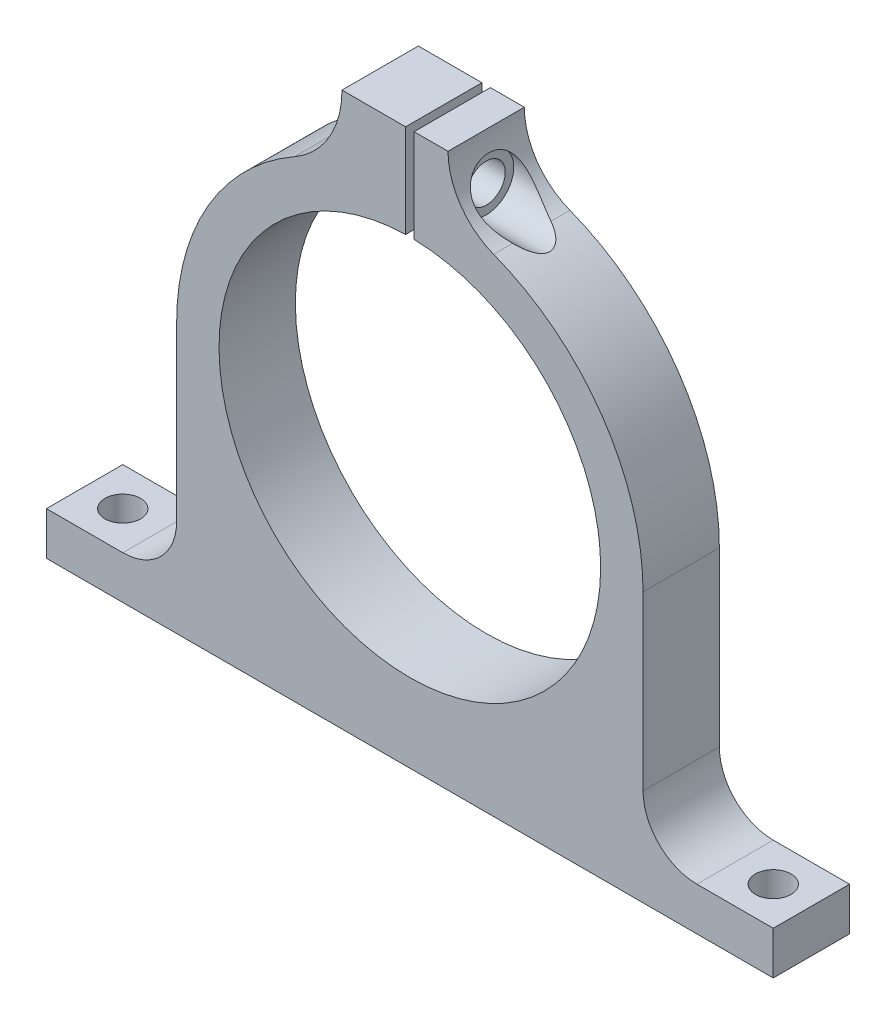
SolidWorks part; units mm, degrees
material "6061-T6 (SS)"
ref_plane "Front Plane" through (0, 0, 0) normal (0, 0, 1) x (1, 0, 0)
ref_plane "Top Plane" through (0, 0, 0) normal (0, 1, 0) x (1, 0, 0)
ref_plane "Right Plane" through (0, 0, 0) normal (1, 0, 0) x (0, 0, -1)
sketch "Sketch1" plane through (0, 0, 0) normal (0, 0, 1) x (1, 0, 0)
  line L0 (0, 0) -> (0, 55) construction
  line L1 (0, 0) -> (85.7, 0) construction
  line L2 (0, 0) -> (-85.7, 0) construction
  line L3 (85.7, -53.34) -> (85.7, -63.5)
  line L4 (85.7, -63.5) -> (-85.7, -63.5)
  line L5 (-85.7, -63.5) -> (-85.7, -53.34)
  line L6 (0, 55) -> (0, 67) construction
  line L7 (0, 67) -> (1, 67) construction
  line L8 (1, 67) -> (1, 44.9889)
  line L9 (1, 67) -> (9, 67)
  line L10 (-45, 0) -> (-55, 0) construction
  line L11 (0, 67) -> (-1, 67) construction
  line L12 (-1, 67) -> (-1, 44.9889)
  line L13 (-1, 67) -> (-16, 67)
  line L14 (-55, 0) -> (-55, -40.64)
  line L15 (-67.7, -53.34) -> (-85.7, -53.34)
  line L16 (55, 0) -> (55, -40.64)
  line L17 (67.7, -53.34) -> (85.7, -53.34)
  arc A0 (-1, 44.9889) -> (1, 44.9889) centre (0, 0) ccw
  arc A1 (55, 0) -> (19.76, 51.3278) centre (0, 0) ccw
  arc A2 (-27.1614, 47.8253) -> (-55, 0) centre (0, 0) ccw
  arc A3 (9, 67) -> (19.76, 51.3278) centre (25.7935, 67) ccw
  arc A4 (55, -40.64) -> (67.7, -53.34) centre (67.7, -40.64) ccw
  arc A5 (-55, -40.64) -> (-67.7, -53.34) centre (-67.7, -40.64) cw
  arc A6 (-27.1614, 47.8253) -> (-16, 67) centre (-38.0513, 67) ccw
  dimension "D1" = 90
  dimension "D3" = 12.7
  dimension "D4" = 18
  dimension "D2" = 10
  dimension "D5" = 10.16
  dimension "D6" = 12
  dimension "D7" = 1
  dimension "D8" = 8
  dimension "D9" = 1
  dimension "D10" = 15
  dimension "D11" = 63.5
extrude "main body" add sketch "Sketch1" along normal blind 18
sketch "Sketch7" plane through (1, 0, 0) normal (-1, 0, 0) x (0, 0, 1)
  line L0 (9, 44.9889) -> (9, 67) construction
  line L1 (18, 44.9889) -> (0, 44.9889) construction
  line L2 (18, 67) -> (0, 67) construction
  circle A0 centre (9, 55.9944) radius 3.5
  dimension "D1" = 7
ref_plane "Plane3" through (9, 0, 0) normal (-1, 0, 0) x (0, 0, 1)
sketch "Sketch10" plane through (9, 0, 0) normal (-1, 0, 0) x (0, 0, 1)
  circle A0 centre (9, 55.9944) radius 6.5
  dimension "D1" = 13
extrude "head counterbore" cut sketch "Sketch10" against normal blind 18
sketch "to table bolt locations" plane through (0, -53.34, 0) normal (0, 1, 0) x (1, 0, 0)
  line L0 (-76.7, 0) -> (-76.7, -18) construction
  line L1 (-67.7, 0) -> (-85.7, 0) construction
  line L2 (-67.7, -18) -> (-85.7, -18) construction
  line L3 (76.7, 0) -> (76.7, -18) construction
  line L4 (85.7, 0) -> (67.7, 0) construction
  line L5 (85.7, -18) -> (67.7, -18) construction
  circle A0 centre (-76.7, -9) radius 4.25
  circle A1 centre (76.7, -9) radius 4.25
  dimension "D1" = 8.5
sketch "Sketch12" plane through (9, 0, 0) normal (-1, 0, 0) x (0, 0, 1)
  line L0 (9, 44.9889) -> (9, 67) construction
  line L1 (18, 44.9889) -> (0, 44.9889) construction
  line L2 (18, 67) -> (0, 67) construction
  circle A0 centre (9, 55.9944) radius 4.25
  dimension "D1" = 8.5
hole_wizard "to table M8 Clearance Hole1" positions "Sketch13" profile "Sketch14" hole size "M8" standard "ANSI Metric" end condition through all
sketch "Sketch13" plane through (0, -53.34, 0) normal (0, 1, 0) x (1, 0, 0)
  point P0 (-76.7, -9)
  point P3 (76.7, -9)
sketch "Sketch14" plane through (-76.7, -53.34, 9) normal (1, 0, 0) x (0, 0, 1)
  line L0 (0, 0) -> (0, 10.16)
  line L1 (0, 10.16) -> (4.2, 10.16)
  line L2 (4.2, 10.16) -> (4.2, 0)
  line L5 (4.2, 0) -> (0, 0)
  line L11 (0, -6.35) -> (0, 107.95) construction
  dimension "Thru Hole Dia." = 8.4
  dimension "Thru Hole Depth" = 10.16
sketch "Sketch15" plane through (-1, 0, 0) normal (1, 0, 0) x (0, 0, -1)
  circle A0 centre (-9, 55.9944) radius 7.9364
hole_wizard "M8x1.25 Tapped Hole1" positions "Sketch18" profile "Sketch19" tap size "M8x1.25" standard "ANSI Metric"
sketch "Sketch18" plane through (-1, 0, 0) normal (1, 0, 0) x (0, 0, -1)
  point P0 (-9, 55.9944)
sketch "Sketch19" plane through (-1, 55.9944, 9) normal (0, 1, 0) x (0, 0, -1)
  line L0 (0, 0) -> (0, 84.7)
  line L1 (0, 84.7) -> (3.4, 84.7)
  line L2 (3.4, 84.7) -> (3.4, 0)
  line L5 (3.4, 0) -> (0, 0)
  line L11 (0, -6.35) -> (0, 107.95) construction
  dimension "Thru Tap Drill Dia." = 6.8
  dimension "Thru Tap Drill Depth" = 84.7
cosmetic thread "Hole Thread1" parameters "D2"=8
hole_wizard "M8 Clearance Hole2" positions "Sketch20" profile "Sketch22" hole size "M8" standard "ANSI Metric"
sketch "Sketch20" plane through (9, 0, 0) normal (-1, 0, 0) x (0, 0, 1)
  point P0 (9, 55.9944)
sketch "Sketch22" plane through (9, 55.9944, 9) normal (0, 1, 0) x (0, 0, -1)
  line L0 (0, 0) -> (0, 10.7029)
  line L1 (0, 10.7029) -> (4.5, 7.999)
  line L2 (4.5, 7.999) -> (4.5, 0)
  line L5 (4.5, 0) -> (0, 0)
  line L10 (0, 10.7029) -> (-4.5, 7.999) construction
  line L11 (0, -6.35) -> (0, 107.95) construction
  dimension "Hole Dia." = 9
  dimension "Hole Depth" = 7.999
  dimension "Drill Angle" = 118
